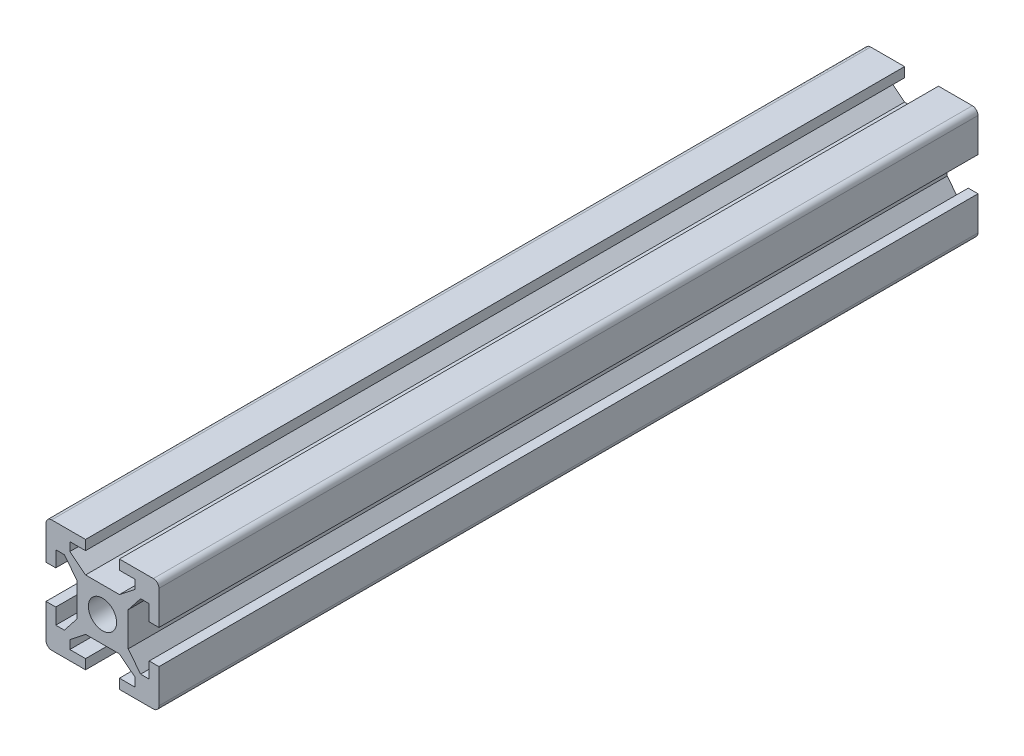
SolidWorks part; units mm, degrees
ref_plane "Front Plane" through (0, 0, 0) normal (0, 0, 1) x (1, 0, 0)
ref_plane "Top Plane" through (0, 0, 0) normal (0, 1, 0) x (1, 0, 0)
ref_plane "Right Plane" through (0, 0, 0) normal (1, 0, 0) x (0, 0, -1)
sketch "Sketch1" plane through (0, 0, 0) normal (0, 0, 1) x (1, 0, 0)
  line L18 (0, 0) -> (0, 20.5117) construction
  line L39 (-10, 10) -> (-3, 10)
  line L41 (10, 10) -> (3, 10)
  line L43 (-10, 10) -> (-10, 3)
  line L45 (-10, -10) -> (-10, -3)
  line L47 (-10, -10) -> (-3, -10)
  line L49 (3, -10) -> (10, -10)
  line L51 (10, -10) -> (10, -3)
  line L53 (10, 3) -> (10, 10)
  line L55 (-3, 10) -> (-3, 8.2726)
  line L56 (-3, 8.2726) -> (-5.7838, 8.2726)
  line L57 (-5.7838, 8.2726) -> (-5.7838, 6.748)
  line L58 (-5.7838, 6.748) -> (-3, 4.5508)
  line L59 (-3, 4.5508) -> (3, 4.5508)
  line L60 (3, 10) -> (3, 8.2726)
  line L61 (3, 8.2726) -> (5.7838, 8.2726)
  line L62 (5.7838, 8.2726) -> (5.7838, 6.748)
  line L63 (5.7838, 6.748) -> (3, 4.5508)
  line L64 (10, 3) -> (8.2726, 3)
  line L65 (8.2726, 3) -> (8.2726, 5.7838)
  line L66 (8.2726, 5.7838) -> (6.748, 5.7838)
  line L67 (10, -3) -> (8.2726, -3)
  line L68 (8.2726, -3) -> (8.2726, -5.7838)
  line L69 (8.2726, -5.7838) -> (6.748, -5.7838)
  line L70 (4.55, -2.9994) -> (4.55, 3.0006)
  line L71 (4.55, -2.9994) -> (6.748, -5.7838)
  line L72 (4.55, 3.0006) -> (6.748, 5.7838)
  line L73 (3, -10) -> (3, -8.2726)
  line L74 (3, -8.2726) -> (5.7838, -8.2726)
  line L75 (5.7838, -8.2726) -> (5.7838, -6.748)
  line L76 (-3, -10) -> (-3, -8.2726)
  line L77 (-3, -8.2726) -> (-5.7838, -8.2726)
  line L78 (-5.7838, -8.2726) -> (-5.7838, -6.748)
  line L79 (2.9994, -4.55) -> (-3.0006, -4.55)
  line L80 (5.7838, -6.748) -> (2.9994, -4.55)
  line L81 (-5.7838, -6.748) -> (-3.0006, -4.55)
  line L82 (-10, -3) -> (-8.2726, -3)
  line L83 (-8.2726, -3) -> (-8.2726, -5.7838)
  line L84 (-8.2726, -5.7838) -> (-6.748, -5.7838)
  line L85 (-10, 3) -> (-8.2726, 3)
  line L86 (-8.2726, 3) -> (-8.2726, 5.7838)
  line L87 (-8.2726, 5.7838) -> (-6.748, 5.7838)
  line L88 (-4.55, -3.0006) -> (-4.55, 2.9994)
  line L89 (-6.748, -5.7838) -> (-4.55, -3.0006)
  line L90 (-4.55, 2.9994) -> (-6.748, 5.7838)
  dimension "D9" = 7
  dimension "D17" = 2.7838
  dimension "D1" = 20
  dimension "D2" = 20
  dimension "D3" = 10
  dimension "D4" = 10
  dimension "D5" = 7
  dimension "D6" = 7
  dimension "D7" = 7
  dimension "D8" = 7
  dimension "D10" = 7
  dimension "D11" = 7
  dimension "D12" = 7
  dimension "D13" = 6
  dimension "D14" = 3
  dimension "D15" = 3.5464
  dimension "D16" = 1.5246
  dimension "D18" = 1.7274
  dimension "D19" = 4.55
  dimension "D20" = 4.55
  dimension "D21" = 4.55
  dimension "D22" = 10
  dimension "D23" = 10
  dimension "D24" = 10
  dimension "D25" = 10
  dimension "D26" = 10
  dimension "D27" = 10
  dimension "D28" = 6
  dimension "D29" = 6
  dimension "D30" = 6
  dimension "D31" = 6
extrude "Boss-Extrude1" add sketch "Sketch1" along normal mid plane 145
sketch "Sketch2" plane through (0, 0, 72.5) normal (0, 0, 1) x (1, 0, 0)
  circle A0 centre (0, 0) radius 2.5
  dimension "D1" = 5
extrude "Cut-Extrude1" cut sketch "Sketch2" against normal through all both and the other way through all
fillet "Fillet1" radius 1 4 edges at (-10, -10, 0) (10, -10, 0) (10, 10, 0) (-10, 10, 0)
